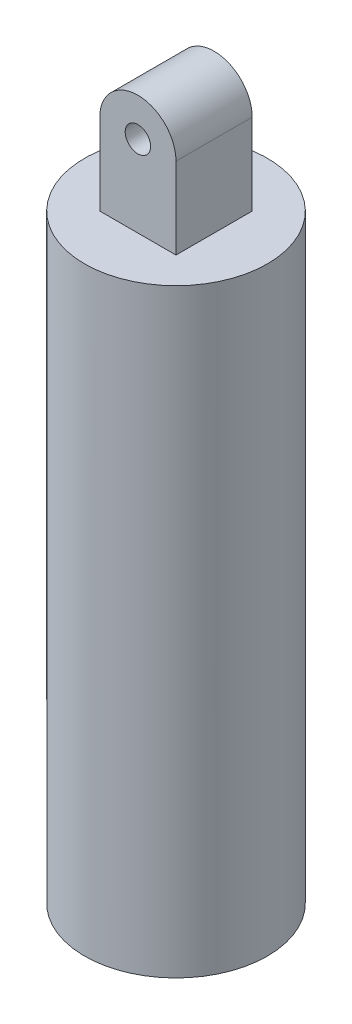
SolidWorks part; units mm, degrees
material "6061-T4 (SS)"
ref_plane "Front Plane" through (0, 0, 0) normal (0, 0, 1) x (1, 0, 0)
ref_plane "Top Plane" through (0, 0, 0) normal (0, 1, 0) x (1, 0, 0)
ref_plane "Right Plane" through (0, 0, 0) normal (1, 0, 0) x (0, 0, -1)
sketch "Sketch1" plane through (0, 0, 0) normal (0, 1, 0) x (1, 0, 0)
  circle A0 centre (0, 0) radius 15
  dimension "D1" = 30
extrude "Extrude-Thin1" add sketch "Sketch1" along normal blind 115 thin
sketch "Sketch2" plane through (0, 115, 0) normal (0, 1, 0) x (1, 0, 0)
  circle A0 centre (0, 0) radius 18
extrude "Boss-Extrude1" add sketch "Sketch2" along normal blind 3
sketch "Sketch3" plane through (0, 0, 0) normal (0, 0, 1) x (1, 0, 0)
  line L0 (0, 118) -> (0, 134) construction
  line L1 (18, 118) -> (-18, 118) construction
  line L2 (-7.5, 118) -> (-7.5, 134)
  line L3 (7.5, 134) -> (7.5, 118)
  line L4 (-7.5, 118) -> (7.5, 118)
  arc A0 (-7.5, 134) -> (7.5, 134) centre (0, 134) cw
  circle A1 centre (0, 134) radius 2.5
  dimension "D2" = 16
  dimension "D3" = 5
  dimension "D1" = 15
extrude "Boss-Extrude2" add sketch "Sketch3" along normal mid plane 15
